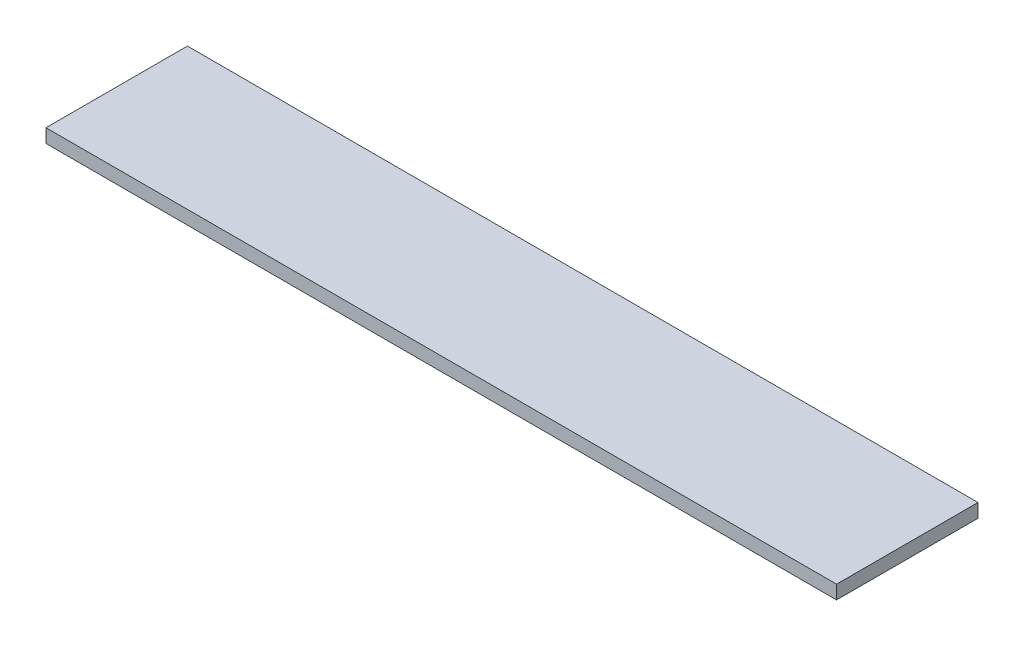
SolidWorks part; units mm, degrees
ref_plane "Front Plane" through (0, 0, 0) normal (0, 0, 1) x (1, 0, 0)
ref_plane "Top Plane" through (0, 0, 0) normal (0, 1, 0) x (1, 0, 0)
ref_plane "Right Plane" through (0, 0, 0) normal (1, 0, 0) x (0, 0, -1)
sketch "Sketch1" plane through (0, 0, 0) normal (0, 1, 0) x (1, 0, 0)
  line L5 (-57.85, 10.35) -> (57.85, 10.35)
  line L6 (-57.85, 10.35) -> (-57.85, -10.35)
  line L7 (-57.85, -10.35) -> (57.85, -10.35)
  line L8 (57.85, 10.35) -> (57.85, -10.35)
  line L9 (-57.85, 10.35) -> (57.85, -10.35) construction
  line L10 (-57.85, -10.35) -> (57.85, 10.35) construction
  point P0 (0, 0)
  dimension "D1" = 115.7
  dimension "D2" = 20.7
extrude "Boss-Extrude1" add sketch "Sketch1" along normal blind 2
